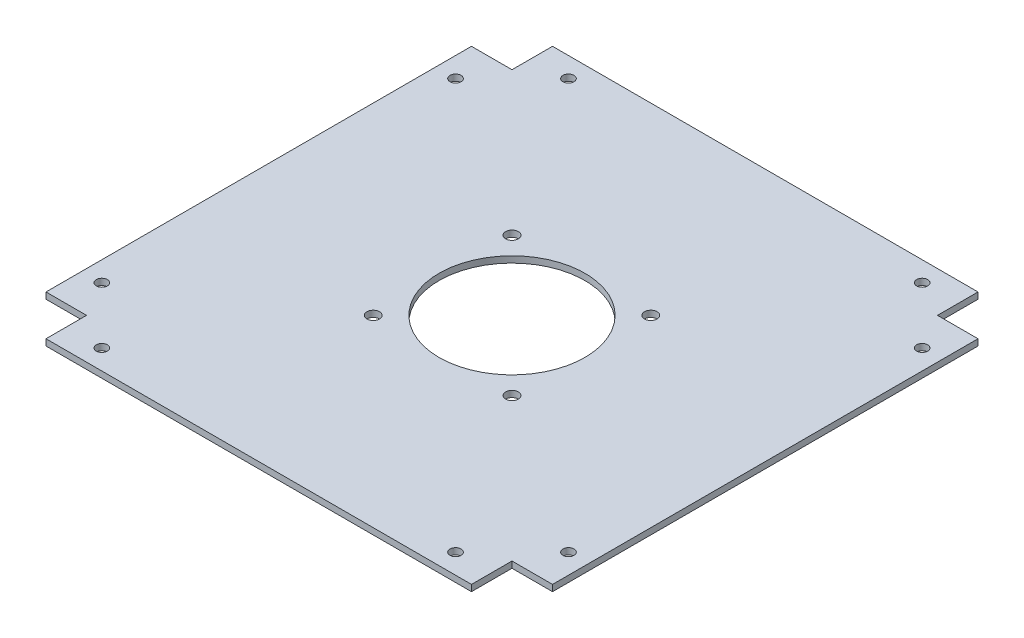
SolidWorks part; units mm, degrees
material "6061-T6 (SS)"
ref_plane "Front Plane" through (0, 0, 0) normal (0, 0, 1) x (1, 0, 0)
ref_plane "Top Plane" through (0, 0, 0) normal (0, 1, 0) x (1, 0, 0)
ref_plane "Right Plane" through (0, 0, 0) normal (1, 0, 0) x (0, 0, -1)
sketch "Sketch1" plane through (0, 0, 0) normal (0, 1, 0) x (1, 0, 0)
  line L1 (-127, -127) -> (127, -127)
  line L2 (-127, -127) -> (-127, 127)
  line L3 (-127, 127) -> (127, 127)
  line L4 (127, -127) -> (127, 127)
  line L5 (-127, -127) -> (127, 127) construction
  line L6 (-127, 127) -> (127, -127) construction
  point P0 (0, 0)
  dimension "D1" = 254
  dimension "D2" = 254
extrude "Boss-Extrude1" add sketch "Sketch1" along normal mid plane 3.175
sketch "Sketch2" plane through (0, 1.5875, 0) normal (0, 1, 0) x (1, 0, 0)
  line L0 (-215.7301, 0) -> (215.7301, 0) construction
  line L1 (0, -166.1777) -> (0, 166.1777) construction
  line L2 (106.68, 106.68) -> (106.68, 127)
  line L3 (-127, 106.68) -> (-106.68, 106.68)
  line L4 (-127, 106.68) -> (-127, 127)
  line L5 (-127, 127) -> (-106.68, 127)
  line L6 (-106.68, 106.68) -> (-106.68, 127)
  line L7 (-127, 106.68) -> (-106.68, 127) construction
  line L8 (-127, 127) -> (-106.68, 106.68) construction
  line L9 (127, 127) -> (106.68, 127)
  line L10 (127, 106.68) -> (127, 127)
  line L11 (127, 106.68) -> (106.68, 106.68)
  line L12 (127, -106.68) -> (106.68, -106.68)
  line L13 (127, -106.68) -> (127, -127)
  line L14 (127, -127) -> (106.68, -127)
  line L15 (106.68, -106.68) -> (106.68, -127)
  line L16 (-127, -106.68) -> (-106.68, -106.68)
  line L17 (-106.68, -106.68) -> (-106.68, -127)
  line L18 (-127, -127) -> (-106.68, -127)
  line L19 (-127, -106.68) -> (-127, -127)
  point P0 (-116.84, 116.84)
  point P4 (0, 0)
  point P8 (0, 0)
  dimension "D1" = 20.32
  dimension "D2" = 20.32
extrude "Cut-Extrude1" cut sketch "Sketch2" against normal blind 3.175
sketch "Sketch3" plane through (0, 1.5875, 0) normal (0, 1, 0) x (1, 0, 0)
  line L0 (-172.9603, 0) -> (172.9603, 0) construction
  line L1 (0, -152.9469) -> (0, 152.9469) construction
  circle A0 centre (0, 0) radius 36.576
  point P4 (0, 0)
  point P8 (0, 0)
  dimension "D1" = 73.152
extrude "Cut-Extrude2" cut sketch "Sketch3" against normal blind 3.175
sketch "Sketch4" plane through (0, 1.5875, 0) normal (0, 1, 0) x (1, 0, 0)
  line L0 (-164.4237, 0) -> (164.4237, 0) construction
  line L1 (0, -132.2762) -> (0, 132.2762) construction
  circle A0 centre (-34.8005, 34.8005) radius 3.175
  circle A1 centre (34.8005, 34.8005) radius 3.175
  circle A2 centre (34.8005, -34.8005) radius 3.175
  circle A3 centre (-34.8005, -34.8005) radius 3.175
  point P5 (0, 0)
  point P9 (0, 0)
  dimension "D1" = 34.8005
  dimension "D2" = 34.8005
  dimension "D3" = 6.35
extrude "Cut-Extrude3" cut sketch "Sketch4" against normal blind 3.175
sketch "Sketch5" plane through (0, 1.5875, 0) normal (0, 1, 0) x (1, 0, 0)
  line L0 (-190.3125, 0) -> (190.3125, 0) construction
  line L1 (0, -153.808) -> (0, 153.808) construction
  line L2 (-127, 106.68) -> (-127, -106.68) construction
  line L3 (-127, 106.68) -> (-106.68, 106.68) construction
  line L4 (-106.68, 106.68) -> (-106.68, 127) construction
  line L5 (106.68, 127) -> (-106.68, 127) construction
  circle A0 centre (-117, 88.68) radius 2.7781
  circle A1 centre (-88.68, 117) radius 2.7781
  circle A2 centre (117, 88.68) radius 2.7781
  circle A3 centre (88.68, 117) radius 2.7781
  circle A4 centre (117, -88.68) radius 2.7781
  circle A5 centre (88.68, -117) radius 2.7781
  circle A6 centre (-88.68, -117) radius 2.7781
  circle A7 centre (-117, -88.68) radius 2.7781
  point P4 (0, 0)
  point P8 (0, 0)
  dimension "D1" = 10
  dimension "D2" = 18
  dimension "D3" = 18
  dimension "D4" = 10
  dimension "D5" = 5.5562
  dimension "D6" = 5.5562
extrude "Cut-Extrude4" cut sketch "Sketch5" against normal blind 3.175
